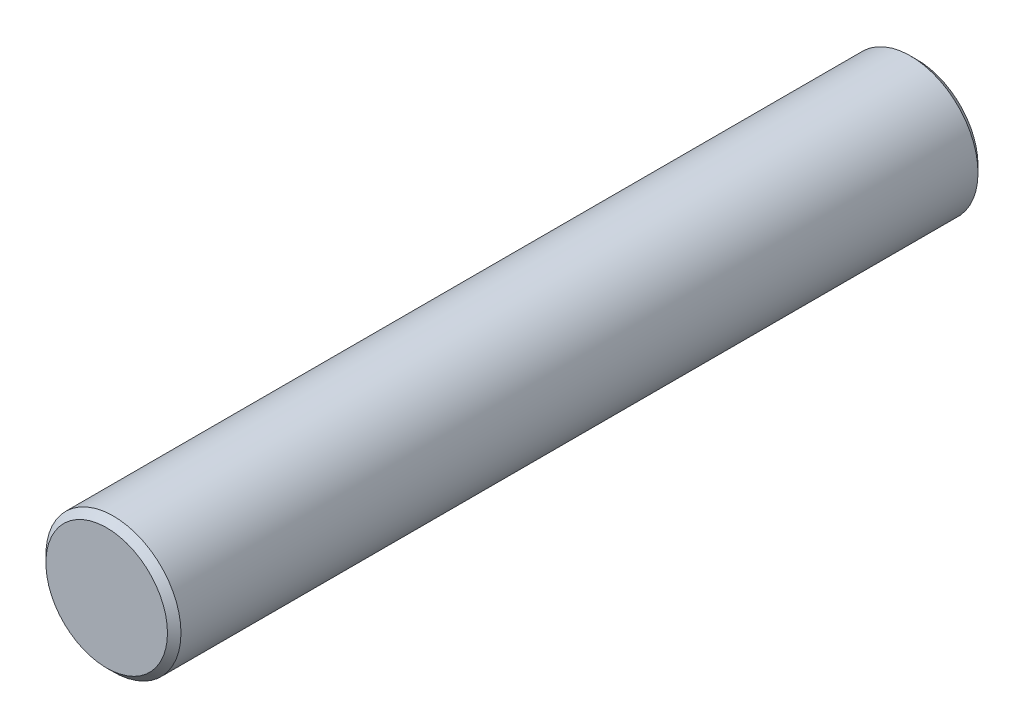
SolidWorks part; units mm, degrees
ref_plane "Front Plane" through (0, 0, 0) normal (0, 0, 1) x (1, 0, 0)
ref_plane "Top Plane" through (0, 0, 0) normal (0, 1, 0) x (1, 0, 0)
ref_plane "Right Plane" through (0, 0, 0) normal (1, 0, 0) x (0, 0, -1)
sketch "Sketch1" plane through (0, 0, 0) normal (0, 0, 1) x (1, 0, 0)
  circle A0 centre (0, 0) radius 1
  dimension "D1" = 2
extrude "Boss-Extrude1" add sketch "Sketch1" along normal mid plane 12 contours A0
chamfer "Chamfer1" distance 0.1 angle 45 2 edges at (1, 0, -6) (1, 0, 6)
